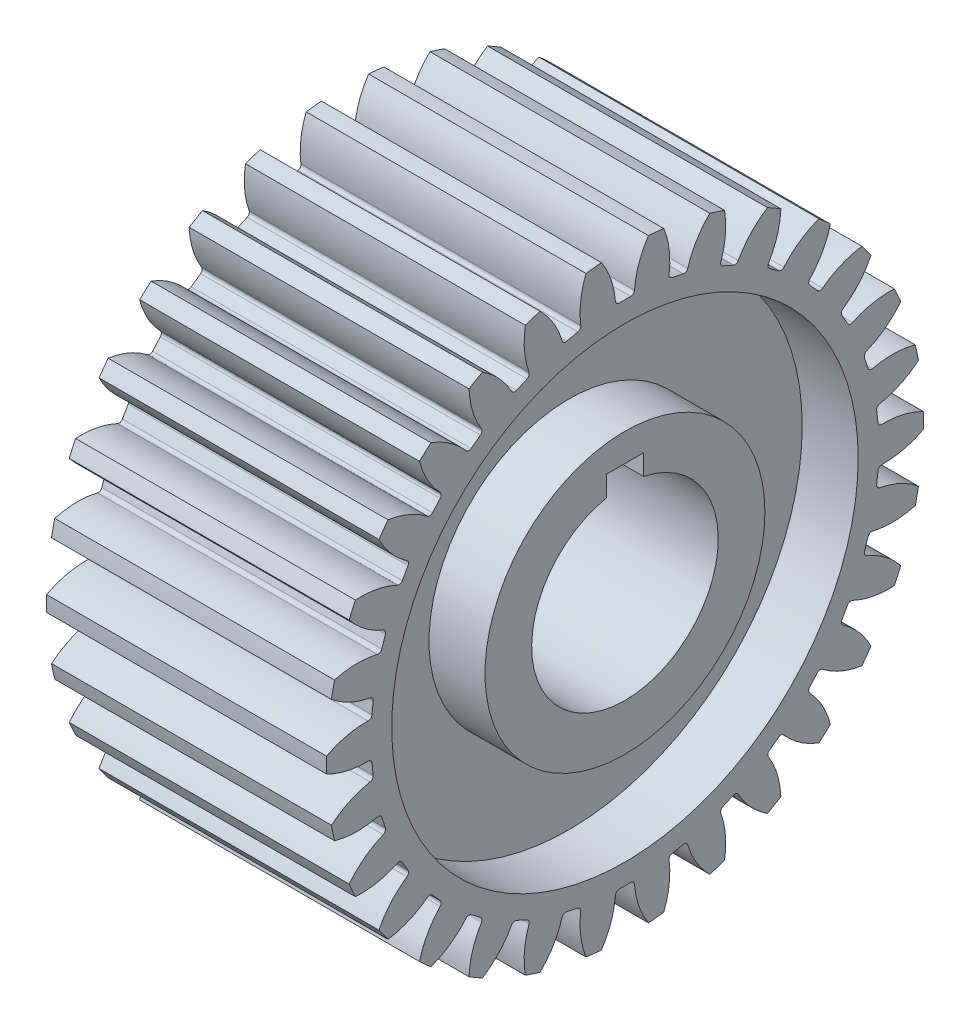
SolidWorks part; units mm, degrees
ref_plane "Front Plane" through (0, 0, 0) normal (0, 0, 1) x (1, 0, 0)
ref_plane "Top Plane" through (0, 0, 0) normal (0, 1, 0) x (1, 0, 0)
ref_plane "Right Plane" through (0, 0, 0) normal (1, 0, 0) x (0, 0, -1)
sketch "Sketch1" plane through (0, 0, 0) normal (1, 0, 0) x (0, 0, -1)
  circle A0 centre (0, 0) radius 16
  dimension "D1" = 32
extrude "circular - extrude" add sketch "Sketch1" along normal mid plane 15
sketch "Sketch3" plane through (7.5, 0, 0) normal (1, 0, 0) x (0, 0, -1)
  line L2 (-1, 4.899) -> (-1, 6)
  line L3 (-1, 6) -> (1, 6)
  line L4 (1, 4.899) -> (1, 6)
  arc A0 (-1, 4.899) -> (1, 4.899) centre (0, 0) ccw
  point P1 (0, 6)
  point P3 (0, 5)
  dimension "D1" = 10
  dimension "D2" = 2
  dimension "D3" = 1
  dimension "D4" = 1
extrude "Cut- circular + top rectangle" cut sketch "Sketch3" against normal through all
sketch "Sketch4" plane through (7.5, 0, 0) normal (1, 0, 0) x (0, 0, -1)
  circle A0 centre (0, 0) radius 7.5
  circle A1 centre (0, 0) radius 12.5
  dimension "D1" = 25
  dimension "D2" = 15
extrude "extrude cut ( rad: 25 -15)" cut sketch "Sketch4" against normal blind 3
mirror "mirror - extrude cut" about plane through (0, 0, 0) normal (1, 0, 0) of "extrude cut ( rad: 25 -15)"
sketch "Sketch5" plane through (7.5, 0, 0) normal (1, 0, 0) x (0, 0, -1)
  line L0 (0, 0) -> (0, 16) construction
  line L1 (0, 16) -> (0, 18.1227) construction
  line L2 (-0.3114, 13.6) -> (0.3114, 13.6)
  line L3 (0.5, 13.6) -> (0.5, 12.49)
  circle A0 centre (0, 0) radius 16 construction
  circle A1 centre (0, 0) radius 12.5 construction
  arc A2 (0.5108, 13.7843) -> (2.08, 16.88) centre (5.0567, 13.4256) cw
  arc A3 (-0.5108, 13.7843) -> (-2.08, 16.88) centre (-5.0567, 13.4256) ccw
  arc A4 (-2.08, 16.88) -> (2.08, 16.88) centre (0, 10.8511) cw
  arc A5 (-0.5108, 13.7843) -> (-0.3114, 13.6) centre (-0.3114, 13.8) ccw
  arc A6 (0.5108, 13.7843) -> (0.3114, 13.6) centre (0.3114, 13.8) cw
  point P14 (0.9894, 15.4873)
  point P16 (0, 13.6)
  point P21 (-0.5, 13.6)
  circle M5 centre (0, 0) radius 16
  dimension "D3" = 1.58
  dimension "D6" = 0.2
  dimension "D7" = 6.3777
  dimension "D1" = 0.5
  dimension "D2" = 13.6
  dimension "D4" = 3.28
  dimension "D5" = 4.56
extrude "Cut - tooth" cut sketch "Sketch5" against normal through all contours A6 A2 A3 A5 L2 M5
pattern_circular "30 nos" count 30 over 360 about axis through (0, 0, 0) along (1, 0, 0) of "Cut - tooth"
